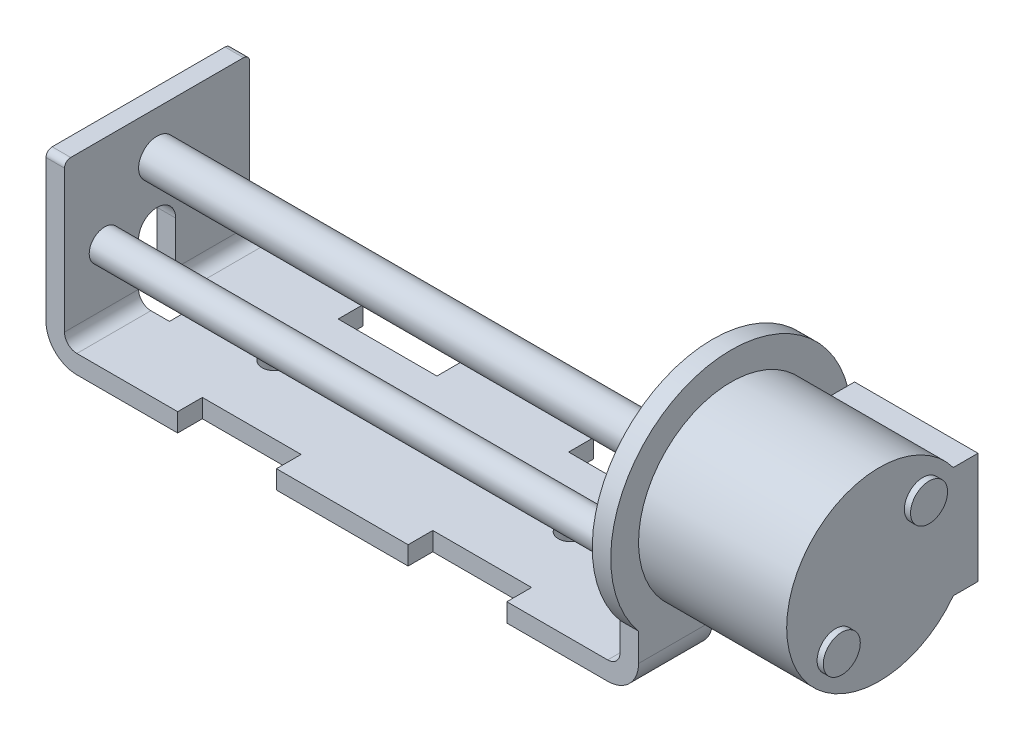
SolidWorks part; units mm, degrees
ref_plane "Front Plane" through (0, 0, 0) normal (0, 0, 1) x (1, 0, 0)
ref_plane "Top Plane" through (0, 0, 0) normal (0, 1, 0) x (1, 0, 0)
ref_plane "Right Plane" through (0, 0, 0) normal (1, 0, 0) x (0, 0, -1)
sketch "Sketch1" plane through (0, 0, 0) normal (0, 0, 1) x (1, 0, 0)
  line L1 (-48, 14.5) -> (0, 14.5)
  line L2 (-48, 14.5) -> (-48, 2.5)
  line L3 (-45.5, 0) -> (-2.5, 0)
  line L4 (0, 14.5) -> (0, 2.5)
  line L5 (-46.5, 14.5) -> (-1.5, 14.5)
  line L6 (-46.5, 14.5) -> (-46.5, 2.5)
  line L7 (-45.5, 1.5) -> (-2.5, 1.5)
  line L8 (-1.5, 14.5) -> (-1.5, 2.5)
  arc A0 (0, 2.5) -> (-2.5, 0) centre (-2.5, 2.5) cw
  arc A1 (-1.5, 2.5) -> (-2.5, 1.5) centre (-2.5, 2.5) cw
  arc A2 (-45.5, 0) -> (-48, 2.5) centre (-45.5, 2.5) cw
  arc A3 (-45.5, 1.5) -> (-46.5, 2.5) centre (-45.5, 2.5) cw
  point P8 (-24, 14.5)
  point P9 (-24, 1.5)
  point P14 (0, 0)
  point P19 (-48, 0)
  dimension "D4" = 1
  dimension "D1" = 48
  dimension "D2" = 45
  dimension "D3" = 14.5
extrude "Boss-Extrude1" add sketch "Sketch1" along normal mid plane 15 contours L7 A3 L6 L1 L2 A2 L3 A0 L4 L8 A1
sketch "Sketch3" plane through (0, 0, 0) normal (1, 0, 0) x (0, 0, -1)
  circle A0 centre (0, 11) radius 9.75
  line M2 (7.5, 2.5) -> (7.5, 14.5)
  line M3 (7.5, 14.5) -> (-7.5, 14.5)
  line M4 (-7.5, 14.5) -> (-7.5, 2.5)
  dimension "D1" = 11
  dimension "D2" = 19.5
extrude "Boss-Extrude2" add sketch "Sketch3" against normal up to surface (1.5 mm away) contours A0 M2 M4 M3
sketch "Sketch4" plane through (0, 0, 0) normal (1, 0, 0) x (0, 0, -1)
  circle A0 centre (0, 11) radius 7.5
  arc A2 (7.5, 4.77) -> (-7.5, 4.77) centre (0, 11) ccw construction
  dimension "D1" = 15
extrude "Boss-Extrude3" add sketch "Sketch4" along normal blind 12
sketch "Sketch5" plane through (-48, 0, 0) normal (-1, 0, 0) x (0, 0, 1)
  line L0 (-7.5, 14.5) -> (-7.5, 2.5) construction
  line L1 (7.5, 14.5) -> (7.5, 2.5) construction
  circle A0 centre (0, 11) radius 1.5
  arc A2 (7.5, 4.77) -> (-7.5, 4.77) centre (0, 11) ccw construction
  circle A3 centre (4.25, 7) radius 1.25
  circle A4 centre (-4.25, 7) radius 1.25
  point P10 (-5.5, 7)
  point P11 (5.5, 7)
  dimension "D1" = 3
  dimension "D2" = 2
  dimension "D4" = 2.5
  dimension "D3" = 2
  dimension "D5" = 4
extrude "Boss-Extrude4" add sketch "Sketch5" against normal up to surface (46.5 mm away) up to face at (-1.5, 7.63, 0)
cosmetic thread "Cosmetic Thread1" parameters "D1"=45, "D2"=2.439
sketch "Sketch6" plane through (0, 0, 0) normal (0, -1, 0) x (1, 0, 0)
  line L0 (-48, 0) -> (0, 0) construction
  line L1 (-48, 7.5) -> (-48, -7.5) construction
  circle A0 centre (-37, 0) radius 1
  circle A1 centre (-13, 0) radius 1
  dimension "D1" = 2
  dimension "D3" = 35
  dimension "D2" = 11
extrude "Cut-Extrude1" cut sketch "Sketch6" against normal up to surface (1.5 mm away) up to face at (-24, 1.5, 0)
sketch "Sketch7" plane through (12, 0, 0) normal (1, 0, 0) x (0, 0, -1)
  line L0 (-5.3033, 5.6967) -> (5.3033, 16.3033) construction
  line L1 (-7.5, 0) -> (7.5, 0) construction
  circle A0 centre (3.5355, 14.5355) radius 1.5
  circle A1 centre (-3.5355, 7.4645) radius 1.5
  circle A2 centre (0, 11) radius 7.5 construction
  point P8 (0, 11)
  dimension "D1" = 3
  dimension "D2" = 45
  dimension "D3" = 5
  dimension "D4" = 5
extrude "Boss-Extrude5" add sketch "Sketch7" along normal blind 0.5
sketch "Sketch8" plane through (0, 1.5, 0) normal (0, 1, 0) x (1, 0, 0)
  line L0 (-45.5, -7.5) -> (-2.5, -7.5) construction
  line L1 (-37.3333, -7.5) -> (-29.3333, -7.5)
  line L2 (-37.3333, -7.5) -> (-37.3333, -5.5)
  line L3 (-37.3333, -5.5) -> (-29.3333, -5.5)
  line L4 (-29.3333, -7.5) -> (-29.3333, -5.5)
  line L5 (-48, -7.5) -> (-37.3333, -7.5) construction
  line L6 (-18.6667, -7.5) -> (-10.6667, -7.5)
  line L7 (-18.6667, -7.5) -> (-18.6667, -5.5)
  line L8 (-18.6667, -5.5) -> (-10.6667, -5.5)
  line L9 (-10.6667, -7.5) -> (-10.6667, -5.5)
  line L10 (-29.3333, -7.5) -> (-18.6667, -7.5) construction
  line L11 (-10.6667, -7.5) -> (0, -7.5) construction
  line L13 (-48, 0) -> (0, 0) construction
  line L14 (-48, -7.5) -> (-48, 7.5) construction
  line L15 (-10.6667, 7.5) -> (0, 7.5) construction
  line L16 (-29.3333, 7.5) -> (-18.6667, 7.5) construction
  line L17 (-48, 7.5) -> (-37.3333, 7.5) construction
  line L18 (-10.6667, 7.5) -> (-10.6667, 5.5)
  line L19 (-18.6667, 5.5) -> (-10.6667, 5.5)
  line L20 (-18.6667, 7.5) -> (-18.6667, 5.5)
  line L21 (-18.6667, 7.5) -> (-10.6667, 7.5)
  line L22 (-29.3333, 7.5) -> (-29.3333, 5.5)
  line L23 (-37.3333, 5.5) -> (-29.3333, 5.5)
  line L24 (-37.3333, 7.5) -> (-37.3333, 5.5)
  line L25 (-37.3333, 7.5) -> (-29.3333, 7.5)
  dimension "D1" = 2
  dimension "D2" = 2
  dimension "D3" = 8
  dimension "D4" = 8
extrude "Cut-Extrude2" cut sketch "Sketch8" against normal through all
fillet "Fillet1" radius 0.5 2 edges at (-47.25, 14.5, 7.5) (-47.25, 14.5, -7.5)
sketch "Sketch9" plane through (-48, 0, 0) normal (-1, 0, 0) x (0, 0, 1)
  line L1 (-1.5, -6) -> (1.5, -6)
  line L2 (-1.5, -6) -> (-1.5, 6)
  line L3 (-1.5, 6) -> (1.5, 6)
  line L4 (1.5, -6) -> (1.5, 6)
  line L5 (0, 6) -> (0, -6) construction
  line L6 (-1.5, 0) -> (1.5, 0) construction
  line L7 (7.5, 0) -> (-7.5, 0) construction
  arc A0 (1.5, 6) -> (-1.5, 6) centre (0, 6) ccw
  circle A2 centre (4.25, 7) radius 1.25 construction
  point P5 (0, 0)
  point P6 (4.25, 7)
  point P7 (0, 0)
  line M11 (-7.5, 2.5) -> (7.5, 2.5)
  dimension "D1" = 1
  dimension "D2" = 3
extrude "Cut-Extrude3" cut sketch "Sketch9" against normal blind 4 contours L3 A0 | L4 L3 L2 M11 | L1 L4 L2 M11
sketch "Sketch10" plane through (0, 0, 0) normal (1, 0, 0) x (0, 0, -1)
  line L0 (-7.5, 0) -> (7.5, 0) construction
  line L1 (1.5, -3) -> (-1.5, -3)
  line L2 (1.5, -3) -> (1.5, 3)
  line L3 (1.5, 3) -> (-1.5, 3)
  line L4 (-1.5, -3) -> (-1.5, 3)
  line L5 (0, 3) -> (0, -3) construction
  line L6 (1.5, 0) -> (-1.5, 0) construction
  point P0 (0, 0)
  dimension "D1" = 3
  dimension "3" = 3
extrude "Cut-Extrude4" cut sketch "Sketch10" against normal blind 4
sketch "Sketch12" plane through (0, 0, 0) normal (0, 0, 1) x (1, 0, 0)
  line L1 (12, 15.5) -> (2, 15.5)
  line L2 (12, 15.5) -> (12, 6.5)
  line L3 (12, 6.5) -> (2, 6.5)
  line L4 (2, 15.5) -> (2, 6.5)
  line L6 (12, 18.5) -> (12, 3.5) construction
  point P4 (0, 0)
  point P7 (12, 11)
  point P9 (2, 11)
  point P12 (0, 0)
  point P13 (0, 0)
  dimension "D1" = 10
  dimension "D2" = 9
extrude "Boss-Extrude6" add sketch "Sketch12" against normal blind 8 contours L1 L4 L3 L2
